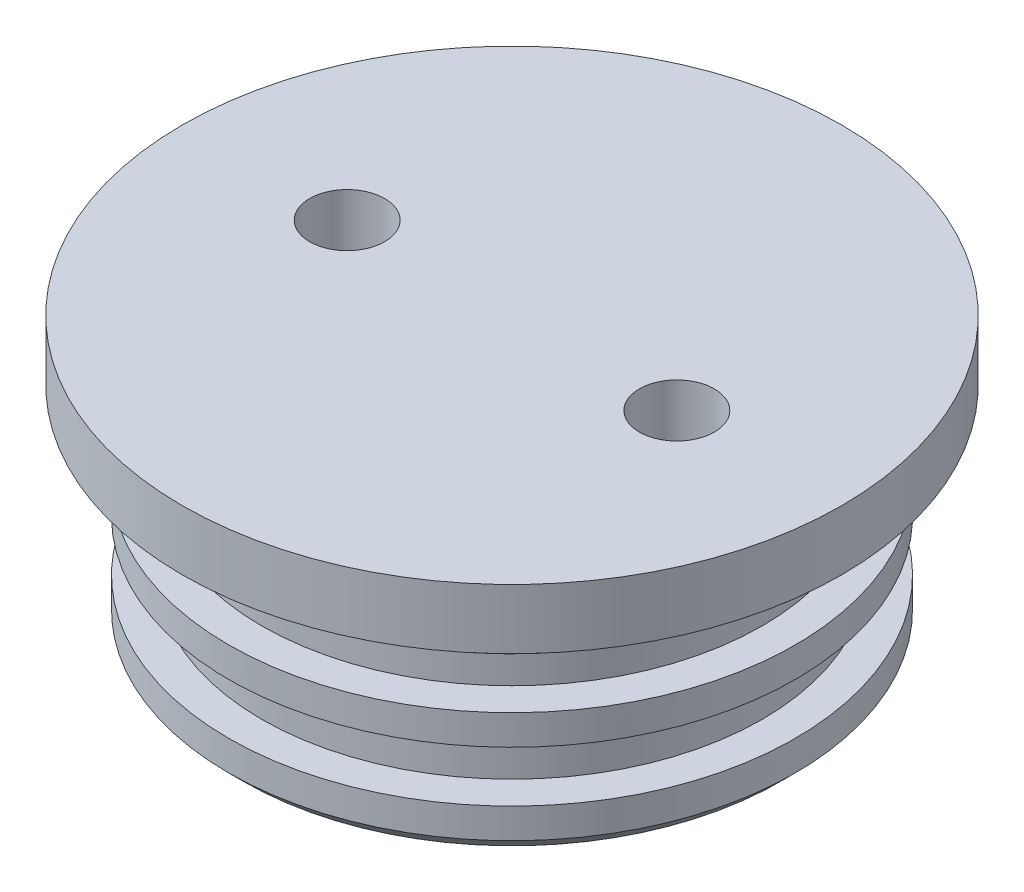
SolidWorks part; units mm, degrees
ref_plane "前视基准面" through (0, 0, 0) normal (0, 0, 1) x (1, 0, 0)
ref_plane "上视基准面" through (0, 0, 0) normal (0, 1, 0) x (1, 0, 0)
ref_plane "右视基准面" through (0, 0, 0) normal (1, 0, 0) x (0, 0, -1)
sketch "草图1" plane through (0, 0, 0) normal (0, 1, 0) x (1, 0, 0)
  circle A0 centre (0, 0) radius 11
  dimension "D1" = 22
extrude "凸台-拉伸1" add sketch "草图1" along normal blind 9
sketch "草图2" plane through (0, 9, 0) normal (0, 1, 0) x (1, 0, 0)
  circle A0 centre (-5.5, 0) radius 0.5
  circle A1 centre (5.5, 0) radius 0.5
  dimension "D1" = 1
  dimension "D2" = 1
  dimension "D3" = 11
  dimension "D4" = 5.5
extrude "切除-拉伸1" cut sketch "草图2" against normal through all
sketch "草图3" plane through (0, 0, 0) normal (0, -1, 0) x (1, 0, 0)
  circle A0 centre (0, 0) radius 9.45
  circle A1 centre (0, 0) radius 16.5491
  dimension "D1" = 18.9
extrude "切除-拉伸2" cut sketch "草图3" against normal blind 7
sketch "草图4" plane through (0, 0, 0) normal (0, 0, 1) x (1, 0, 0)
  line L0 (-9.45, 7) -> (-9.45, 0) construction
  line L1 (-10.55, 5.9) -> (-8.35, 5.9)
  line L2 (-10.55, 5.9) -> (-10.55, 4.2)
  line L3 (-10.55, 4.2) -> (-8.35, 4.2)
  line L4 (-8.35, 5.9) -> (-8.35, 4.2)
  line L5 (-10.55, 5.9) -> (-8.35, 4.2) construction
  line L6 (-10.55, 4.2) -> (-8.35, 5.9) construction
  line L7 (-9.45, 0) -> (9.45, 0) construction
  line L8 (-10.55, 3.2) -> (-8.35, 3.2)
  line L9 (-10.55, 3.2) -> (-10.55, 1.5)
  line L10 (-10.55, 1.5) -> (-8.35, 1.5)
  line L11 (-8.35, 3.2) -> (-8.35, 1.5)
  line L12 (-10.55, 3.2) -> (-8.35, 1.5) construction
  line L13 (-10.55, 1.5) -> (-8.35, 3.2) construction
  line L14 (0, 0) -> (0, 12.2991) construction
  line L15 (-9.45, 7) -> (9.45, 7) construction
  point P0 (-9.45, 5.05)
  point P7 (-9.45, 2.35)
  dimension "D1" = 1.7
  dimension "D2" = 1.7
  dimension "D3" = 1.5
  dimension "D4" = 1
  dimension "D5" = 2.2
  dimension "D6" = 2.2
  dimension "D7" = 1.1
revolve "切除-旋转1" cut sketch "草图4" angle 360 about L14
sketch "草图5" plane through (0, 0, 0) normal (0, -1, 0) x (1, 0, 0)
  circle A0 centre (0, 0) radius 3
  point P0 (0, 0)
  dimension "D3" = 6
extrude "切除-拉伸3" cut sketch "草图5" against normal blind 7
sketch "草图6" plane through (0, 9, 0) normal (0, 1, 0) x (1, 0, 0)
  circle A0 centre (0, 0) radius 1.4
  dimension "D1" = 2.8
extrude "切除-拉伸4" [suppressed] cut sketch "草图6" against normal blind 7
sketch "草图7" plane through (0, 9, 0) normal (0, 1, 0) x (1, 0, 0)
  circle A0 centre (-5.5, 0) radius 1.25
  circle A1 centre (5.5, 0) radius 1.25
  dimension "D1" = 2.5
  dimension "D2" = 2.5
extrude "切除-拉伸5" cut sketch "草图7" against normal blind 2.5
sketch "草图8" plane through (0, 0, 0) normal (0, -1, 0) x (1, 0, 0)
  circle A0 centre (-5.5, 0) radius 1.25
  circle A1 centre (5.5, 0) radius 1.25
  dimension "D1" = 2.5
  dimension "D2" = 2.5
extrude "切除-拉伸6" cut sketch "草图8" against normal blind 1.5
sketch "草图9" plane through (0, 0, 0) normal (0, -1, 0) x (1, 0, 0)
  circle A0 centre (0, 0) radius 3
  circle A1 centre (0, 0) radius 4
  dimension "D1" = 6
  dimension "D2" = 8
extrude "切除-拉伸7" cut sketch "草图9" against normal blind 2
chamfer "倒角1" distance 0.5 angle 45 1 edges at (0, 0, -9.45)
